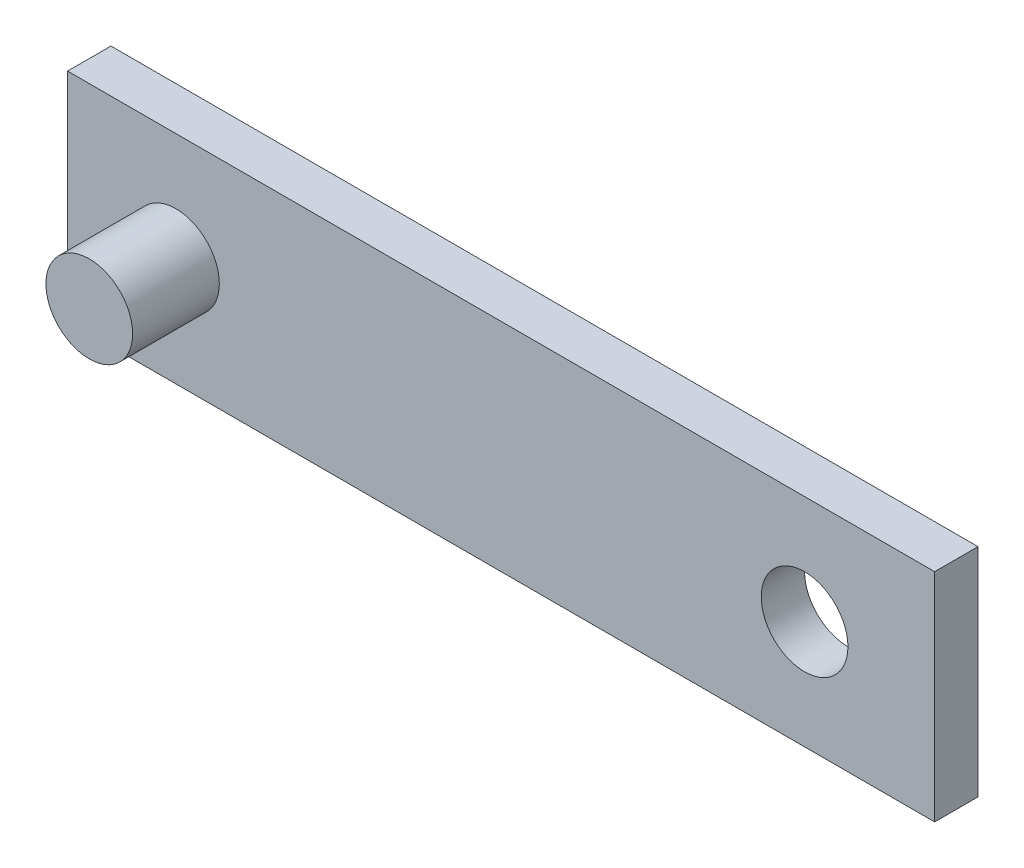
SolidWorks part; units mm, degrees
ref_plane "Front Plane" through (0, 0, 0) normal (0, 0, 1) x (1, 0, 0)
ref_plane "Top Plane" through (0, 0, 0) normal (0, 1, 0) x (1, 0, 0)
ref_plane "Right Plane" through (0, 0, 0) normal (1, 0, 0) x (0, 0, -1)
sketch "Sketch1" plane through (0, 0, 0) normal (0, 0, 1) x (1, 0, 0)
  line L1 (0, 0) -> (-100, 0)
  line L2 (0, 0) -> (0, 25)
  line L3 (0, 25) -> (-100, 25)
  line L4 (-100, 0) -> (-100, 25)
  circle A0 centre (-15, 12.5) radius 5
  dimension "D5" = 10
  dimension "D1" = 100
  dimension "D2" = 25
  dimension "D3" = 15
  dimension "D4" = 12.5
extrude "Boss-Extrude1" add sketch "Sketch1" along normal blind 5
sketch "Sketch2" plane through (0, 0, 5) normal (0, 0, 1) x (1, 0, 0)
  line L0 (0, 25) -> (-100, 25) construction
  line L1 (-100, 25) -> (-100, 0) construction
  circle A0 centre (-87.5, 12.5) radius 5
  dimension "D1" = 10
  dimension "D2" = 12.5
  dimension "D3" = 12.5
extrude "Boss-Extrude2" add sketch "Sketch2" along normal blind 10
